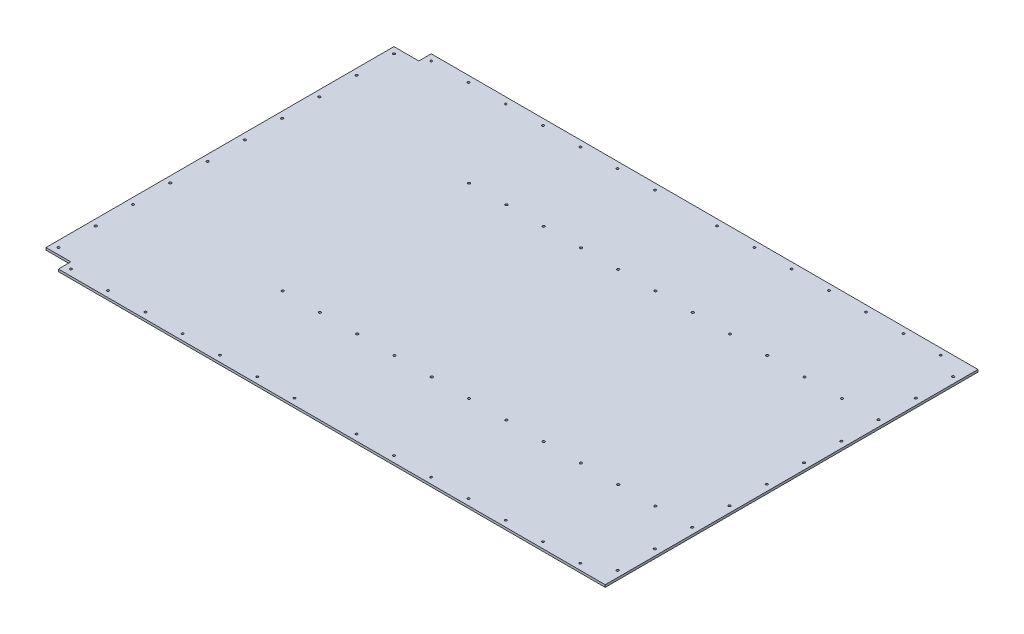
SolidWorks part; units mm, degrees
ref_plane "Front Plane" through (0, 0, 0) normal (0, 0, 1) x (1, 0, 0)
ref_plane "Top Plane" through (0, 0, 0) normal (0, 1, 0) x (1, 0, 0)
ref_plane "Right Plane" through (0, 0, 0) normal (1, 0, 0) x (0, 0, -1)
sketch "Sketch1" plane through (0, 0, 0) normal (0, 1, 0) x (1, 0, 0)
  line L1 (-584.2, 381) -> (584.2, 381)
  line L2 (-584.2, 381) -> (-584.2, -381)
  line L3 (-584.2, -381) -> (584.2, -381)
  line L4 (584.2, 381) -> (584.2, -381)
  line L5 (-584.2, 381) -> (584.2, -381) construction
  line L6 (-584.2, -381) -> (584.2, 381) construction
  point P0 (0, 0)
  dimension "D1" = 762
  dimension "D2" = 1168.4
extrude "Boss-Extrude1" add sketch "Sketch1" along normal blind 4.7625
sketch "Sketch2" plane through (0, 4.7625, 0) normal (0, 1, 0) x (1, 0, 0)
  line L0 (-584.2, 0) -> (584.2, 0) construction
  line L1 (-584.2, 381) -> (-533.4, 381)
  line L2 (-584.2, 381) -> (-584.2, 355.6)
  line L3 (-584.2, 355.6) -> (-533.4, 355.6)
  line L4 (-533.4, 381) -> (-533.4, 355.6)
  line L5 (-584.2, 381) -> (-584.2, -381) construction
  line L6 (584.2, -381) -> (584.2, 381) construction
  line L7 (-533.4, -381) -> (-533.4, -355.6)
  line L8 (-584.2, -355.6) -> (-533.4, -355.6)
  line L9 (-584.2, -381) -> (-584.2, -355.6)
  line L10 (-584.2, -381) -> (-533.4, -381)
  dimension "D1" = 50.8
  dimension "D2" = 25.4
extrude "Cut-Extrude1" cut sketch "Sketch2" against normal through all
sketch "Sketch3" plane through (0, 4.7625, 0) normal (0, 1, 0) x (1, 0, 0)
  line L0 (-533.4, -381) -> (584.2, -381) construction
  line L1 (-584.2, 0) -> (584.2, 0) construction
  line L2 (-584.2, 355.6) -> (-584.2, -355.6) construction
  line L3 (584.2, -381) -> (584.2, 381) construction
  circle A0 centre (-265.5245, -190.5) radius 2.413
  circle A1 centre (-189.3245, -190.5) radius 2.413
  circle A2 centre (-113.1245, -190.5) radius 2.413
  circle A3 centre (-36.9245, -190.5) radius 2.413
  circle A4 centre (39.2755, -190.5) radius 2.413
  circle A5 centre (115.4755, -190.5) radius 2.413
  circle A6 centre (191.6755, -190.5) radius 2.413
  circle A7 centre (267.8755, -190.5) radius 2.413
  circle A8 centre (344.0755, -190.5) radius 2.413
  circle A9 centre (420.2755, -190.5) radius 2.413
  circle A10 centre (496.4755, -190.5) radius 2.413
  circle A11 centre (496.4755, 190.5) radius 2.413
  circle A12 centre (420.2755, 190.5) radius 2.413
  circle A13 centre (344.0755, 190.5) radius 2.413
  circle A14 centre (267.8755, 190.5) radius 2.413
  circle A15 centre (191.6755, 190.5) radius 2.413
  circle A16 centre (115.4755, 190.5) radius 2.413
  circle A17 centre (39.2755, 190.5) radius 2.413
  circle A18 centre (-36.9245, 190.5) radius 2.413
  circle A19 centre (-113.1245, 190.5) radius 2.413
  circle A20 centre (-189.3245, 190.5) radius 2.413
  circle A21 centre (-265.5245, 190.5) radius 2.413
  dimension "D1" = 4.826
  dimension "D2" = 190.5
  dimension "D3" = 11
extrude "Cut-Extrude2" cut sketch "Sketch3" against normal through all
sketch "Sketch4" plane through (0, 4.7625, 0) normal (0, 1, 0) x (1, 0, 0)
  line L0 (-584.2, 355.6) -> (-584.2, -355.6) construction
  line L1 (-584.2, 355.6) -> (-533.4, 355.6) construction
  line L2 (-584.2, 0) -> (584.2, 0) construction
  line L3 (584.2, -381) -> (584.2, 381) construction
  line L4 (0, 381) -> (0, -381) construction
  line L5 (584.2, 381) -> (-533.4, 381) construction
  line L6 (-533.4, -381) -> (584.2, -381) construction
  line L7 (-533.4, 355.6) -> (-533.4, 381) construction
  circle A0 centre (-571.5, 342.9) radius 2.413
  circle A1 centre (-571.5, 266.7) radius 2.413
  circle A2 centre (-571.5, 190.5) radius 2.413
  circle A3 centre (-571.5, 114.3) radius 2.413
  circle A4 centre (-571.5, 38.1) radius 2.413
  circle A5 centre (-571.5, -38.1) radius 2.413
  circle A6 centre (-571.5, -114.3) radius 2.413
  circle A7 centre (-571.5, -190.5) radius 2.413
  circle A8 centre (-571.5, -266.7) radius 2.413
  circle A9 centre (-571.5, -342.9) radius 2.413
  circle A10 centre (-520.7, 368.3) radius 2.1927
  circle A11 centre (-444.5, 368.3) radius 2.1927
  circle A12 centre (-368.3, 368.3) radius 2.1927
  circle A13 centre (-292.1, 368.3) radius 2.1927
  circle A14 centre (-215.9, 368.3) radius 2.1927
  circle A15 centre (-139.7, 368.3) radius 2.1927
  circle A16 centre (-63.5, 368.3) radius 2.1927
  circle A17 centre (-63.5, -368.3) radius 2.1927
  circle A18 centre (-139.7, -368.3) radius 2.1927
  circle A19 centre (-215.9, -368.3) radius 2.1927
  circle A20 centre (-292.1, -368.3) radius 2.1927
  circle A21 centre (-368.3, -368.3) radius 2.1927
  circle A22 centre (-444.5, -368.3) radius 2.1927
  circle A23 centre (-520.7, -368.3) radius 2.1927
  circle A24 centre (520.7, -368.3) radius 2.1927
  circle A25 centre (444.5, -368.3) radius 2.1927
  circle A26 centre (368.3, -368.3) radius 2.1927
  circle A27 centre (292.1, -368.3) radius 2.1927
  circle A28 centre (215.9, -368.3) radius 2.1927
  circle A29 centre (139.7, -368.3) radius 2.1927
  circle A30 centre (63.5, -368.3) radius 2.1927
  circle A31 centre (63.5, 368.3) radius 2.1927
  circle A32 centre (139.7, 368.3) radius 2.1927
  circle A33 centre (215.9, 368.3) radius 2.1927
  circle A34 centre (292.1, 368.3) radius 2.1927
  circle A35 centre (368.3, 368.3) radius 2.1927
  circle A36 centre (444.5, 368.3) radius 2.1927
  circle A37 centre (520.7, 368.3) radius 2.1927
  circle A38 centre (571.5, -342.9) radius 2.413
  circle A39 centre (571.5, -266.7) radius 2.413
  circle A40 centre (571.5, -190.5) radius 2.413
  circle A41 centre (571.5, -114.3) radius 2.413
  circle A42 centre (571.5, -38.1) radius 2.413
  circle A43 centre (571.5, 38.1) radius 2.413
  circle A44 centre (571.5, 114.3) radius 2.413
  circle A45 centre (571.5, 190.5) radius 2.413
  circle A46 centre (571.5, 266.7) radius 2.413
  circle A47 centre (571.5, 342.9) radius 2.413
  dimension "D1" = 4.826
  dimension "D2" = 12.7
  dimension "D3" = 12.7
  dimension "D5" = 12.7
  dimension "D6" = 12.7
  dimension "D4" = 5
  dimension "D7" = 7
extrude "Cut-Extrude3" cut sketch "Sketch4" against normal through all
